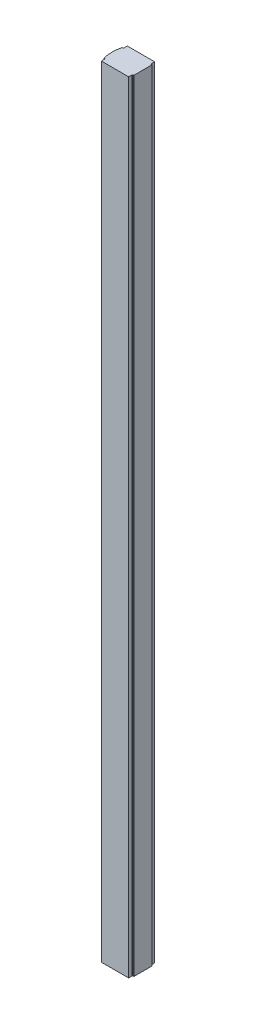
SolidWorks part; units mm, degrees
ref_plane "Alzado" through (0, 0, 0) normal (0, 0, 1) x (1, 0, 0)
ref_plane "Planta" through (0, 0, 0) normal (0, 1, 0) x (1, 0, 0)
ref_plane "Vista lateral" through (0, 0, 0) normal (1, 0, 0) x (0, 0, -1)
sketch "Croquis1" plane through (0, 0, 0) normal (0, 1, 0) x (1, 0, 0)
  line L1 (0, 0) -> (21, 0)
  line L2 (0, 0) -> (0, 2.5)
  line L3 (0, 20) -> (21, 20)
  line L4 (22, 3) -> (22, 17)
  line L8 (22, 17) -> (21.5, 17)
  line L9 (21, 17.5) -> (21, 20)
  line L10 (22, 3) -> (21.5, 3)
  line L11 (21, 2.5) -> (21, 0)
  line L12 (10.5, 20) -> (10.5, 0) construction
  line L13 (0, 2.5) -> (0, 0)
  line L14 (-1, 3) -> (-0.5, 3)
  line L15 (-1, 17) -> (-0.5, 17)
  line L16 (0, 17.5) -> (0, 20)
  line L17 (0, 17.5) -> (0, 20)
  arc A6 (22, 17) -> (22, 3) centre (-7.1719, 10) cw
  arc A7 (21.5, 17) -> (21, 17.5) centre (21.5, 17.5) cw
  arc A8 (21, 2.5) -> (21.5, 3) centre (21.5, 2.5) cw
  arc A9 (0, 2.5) -> (-0.5, 3) centre (-0.5, 2.5) ccw
  arc A10 (-1, 17) -> (-1, 3) centre (28.1719, 10) ccw
  arc A11 (-0.5, 17) -> (0, 17.5) centre (-0.5, 17.5) ccw
  point P24 (22.8281, 10)
  dimension "D5" = 30
  dimension "D8" = 0.5
  dimension "D9" = 0.5
  dimension "D6" = 14
  dimension "D7" = 10
extrude "Saliente-Extruir1" add sketch "Croquis1" along normal blind 600 contours L12 L3 L16 A11 L15 A10 L14 A9 L2 L1 | L3 L12 L1 L11 A8 L10 L4 L8 A7 L9
